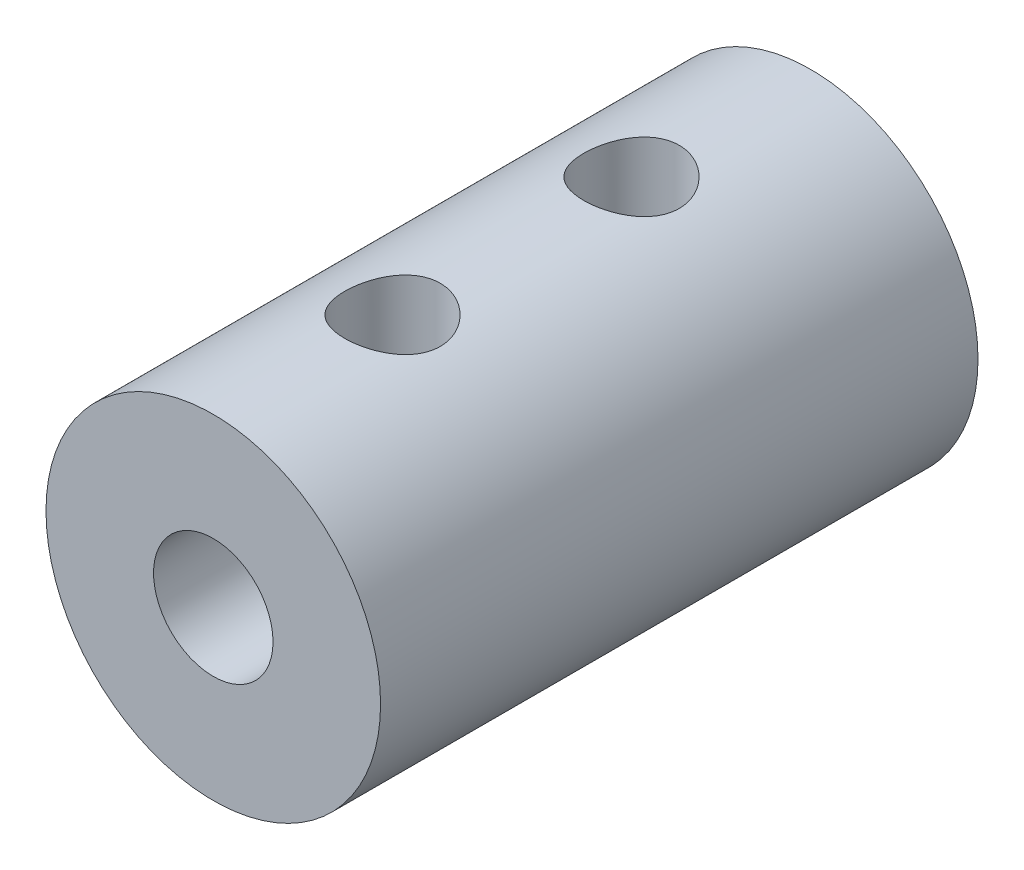
SolidWorks part; units mm, degrees
ref_plane "Front Plane" through (0, 0, 0) normal (0, 0, 1) x (1, 0, 0)
ref_plane "Top Plane" through (0, 0, 0) normal (0, 1, 0) x (1, 0, 0)
ref_plane "Right Plane" through (0, 0, 0) normal (1, 0, 0) x (0, 0, -1)
sketch "Sketch1" plane through (0, 0, 0) normal (0, 0, 1) x (1, 0, 0)
  circle A0 centre (0, 0) radius 7
  circle A1 centre (0, 0) radius 4
  dimension "D1" = 8
  dimension "D2" = 14
extrude "Boss-Extrude1" add sketch "Sketch1" along normal blind 25
sketch "Sketch2" plane through (0, 0, 25) normal (0, 0, 1) x (1, 0, 0)
  circle A0 centre (0, 0) radius 4
  circle A1 centre (0, 0) radius 2.5
  dimension "D1" = 5
  dimension "D2" = 8
extrude "Boss-Extrude2" add sketch "Sketch2" against normal blind 12.5
sketch "Sketch3" plane through (0, 0, 0) normal (0, 1, 0) x (1, 0, 0)
  line L0 (-7, -25) -> (7, -25) construction
  line L1 (7, 0) -> (-7, 0) construction
  line L2 (0, -7.5) -> (0, 0) construction
  line L3 (0, -17.5) -> (0, -25) construction
  circle A0 centre (0, -7.5) radius 2
  circle A1 centre (0, -17.5) radius 2
  dimension "D1" = 7.5
  dimension "D2" = 7.5
  dimension "D3" = 4
  dimension "D4" = 4
extrude "Cut-Extrude1" cut sketch "Sketch3" against normal through all both and the other way through all
